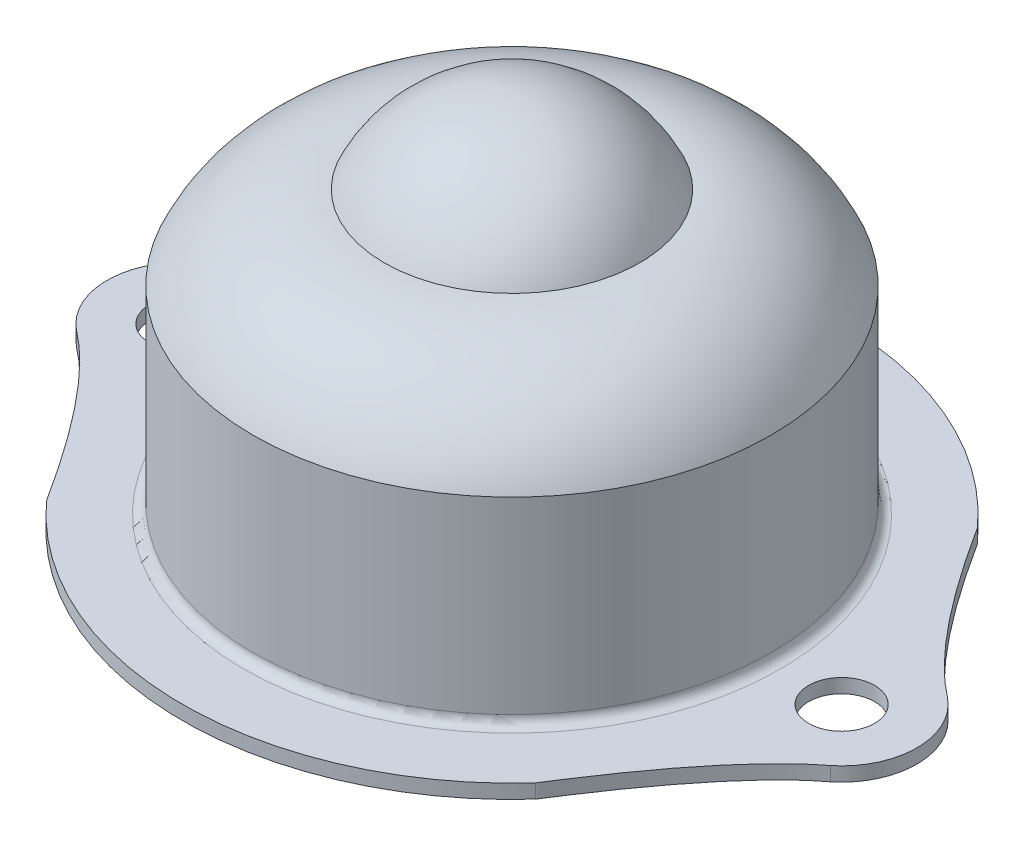
SolidWorks part; units mm, degrees
ref_plane "Front Plane" through (0, 0, 0) normal (0, 0, 1) x (1, 0, 0)
ref_plane "Top Plane" through (0, 0, 0) normal (0, 1, 0) x (1, 0, 0)
ref_plane "Right Plane" through (0, 0, 0) normal (1, 0, 0) x (0, 0, -1)
sketch "Sketch1" plane through (0, 0, 0) normal (0, 1, 0) x (1, 0, 0)
  circle A0 centre (0, 0) radius 26
  circle A2 centre (-35, 0) radius 3.5
  arc A3 (25.9663, 23.4681) -> (-25.9663, 23.4681) centre (0, 0) ccw
  arc A6 (-40.0283, 6.2223) -> (-40.0283, -6.2223) centre (-35, 0) ccw
  arc A8 (40.0283, 6.2223) -> (40.0283, -6.2223) centre (35, 0) cw
  circle A9 centre (35, 0) radius 3.5
  arc A10 (25.9663, -23.4681) -> (-25.9663, -23.4681) centre (0, 0) cw
  spline S0 degree 3 poles (-40.0283, 6.2223) (-33.3096, 11.2703) (-26.1791, 23.2437) (-25.9663, 23.4681) knots 0 0 0 0 1 1 1 1
  spline S1 degree 3 poles (40.0283, 6.2223) (33.3096, 11.2703) (26.1791, 23.2437) (25.9663, 23.4681) knots 0 0 0 0 1 1 1 1
  spline S2 degree 3 poles (40.0283, -6.2223) (33.3096, -11.2703) (26.1791, -23.2437) (25.9663, -23.4681) knots 0 0 0 0 1 1 1 1
  spline S3 degree 3 poles (-40.0283, -6.2223) (-33.3096, -11.2703) (-26.1791, -23.2437) (-25.9663, -23.4681) knots 0 0 0 0 1 1 1 1
  dimension "D1" = 52
  dimension "D3" = 7
  dimension "D6" = 70
  dimension "D9" = 16
  dimension "D4" = 35
extrude "Boss-Extrude1" add sketch "Sketch1" along normal blind 1.5
sketch "Sketch2" plane through (0, 0, 0) normal (1, 0, 0) x (0, 0, -1)
  line L0 (-26, 1.5) -> (-26, 22.5)
  line L1 (-27.5, 1.5) -> (-27.5, 22.5)
  line L2 (-23.4681, 1.5) -> (-35, 1.5) construction
  line L3 (-23.4681, 0) -> (-6.2223, 0) construction
  line L4 (-27.5, 1.5) -> (-26, 1.5)
  line L5 (0, 40) -> (0, 10)
  arc A0 (0, 40) -> (0, 10) centre (0, 25) ccw
  arc A1 (-14.1421, 30) -> (-26, 22.5) centre (-12.9839, 15.0448) ccw
  arc A2 (-27.5, 22.5) -> (-13.5721, 31.3874) centre (-13.7617, 16.3273) cw
  dimension "D2" = 40
  dimension "D3" = 15
  dimension "D4" = 30
  dimension "D5" = 26
  dimension "D6" = 15
  dimension "D8" = 1.5
  dimension "D11" = 1.5
  dimension "D1" = 21
  dimension "D7" = 21
  dimension "D9" = 1.5
  dimension "D10" = 1.5
  dimension "D12" = 1.5
  dimension "D13" = 30
ref_axis "Axis1" through (0, 42, 0) along (0, -1, 0)
revolve "Revolve1" add sketch "Sketch2" angle 360 about axis through (0, 42, 0) along (0, -1, 0)
sketch "Sketch3" plane through (0, 0, 0) normal (0, 0, 1) x (1, 0, 0)
  line L0 (0, 42) -> (0, -2) construction
  line L1 (26, 22.5) -> (-26, 22.5) construction
  line L2 (0, 1.5) -> (0, 0)
  line L3 (-25.9663, 0) -> (-24.4663, 0)
  line L4 (-26, 0) -> (26, 0) construction
  line L5 (-24.4663, 0) -> (-24.5, 20.9856)
  line L6 (-25.9663, 0) -> (-25.9663, 22.5)
  line L7 (-25.9663, 22.5) -> (-23.181, 22.5)
  arc A0 (0, 0) -> (-24.5, 20.9856) centre (0, 24.7943) cw
  arc A1 (0, 1.5) -> (-23.181, 22.5) centre (0, 24.7943) cw
  dimension "D1" = 24.5
  dimension "D2" = 1.5
  dimension "D3" = 1.5
  dimension "D4" = 1.5
  dimension "D5" = 20.9856
  dimension "D6" = 22.5
  dimension "D7" = 2.7853
revolve "Revolve2" add sketch "Sketch3" angle 360 about axis through (0, 42, 0) along (0, -1, 0)
fillet "Fillet1" radius 1 1 edges at (0, 1.5, 27.5)
